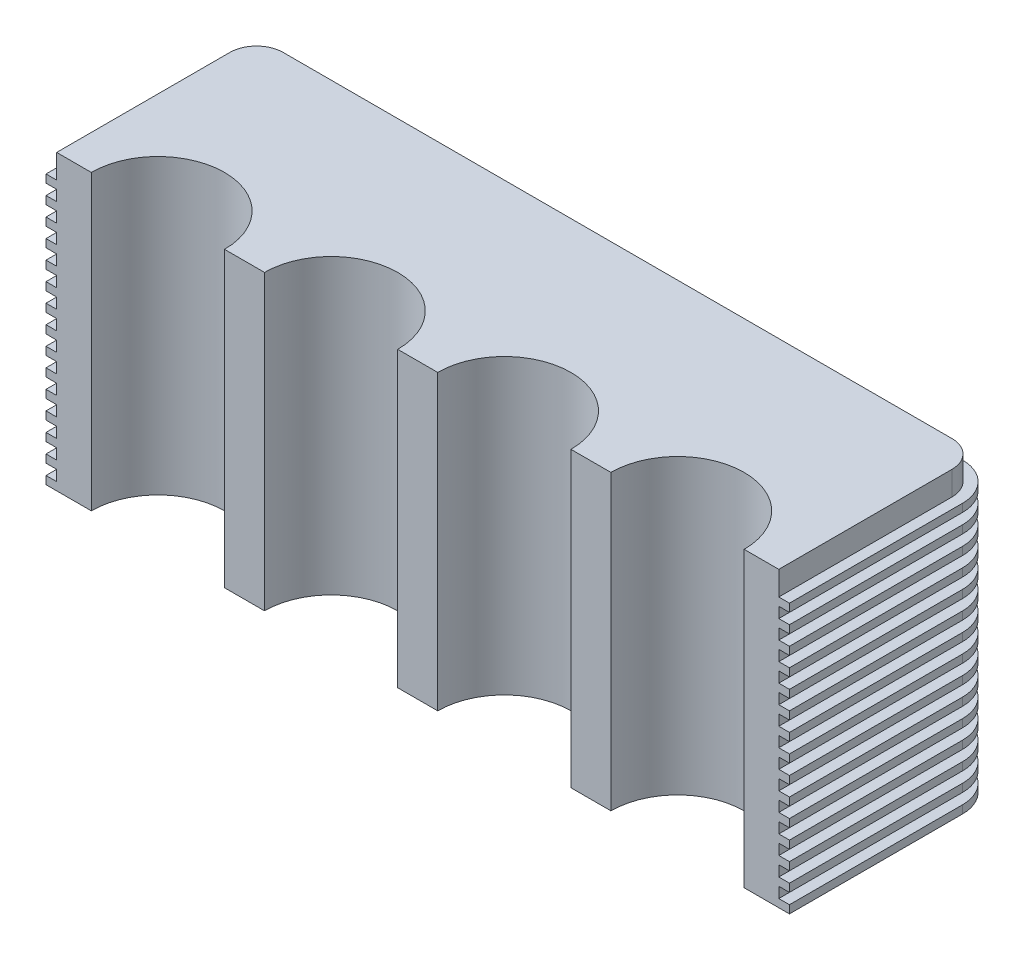
SolidWorks part; units mm, degrees
ref_plane "Front Plane" through (0, 0, 0) normal (0, 0, 1) x (1, 0, 0)
ref_plane "Top Plane" through (0, 0, 0) normal (0, 1, 0) x (1, 0, 0)
ref_plane "Right Plane" through (0, 0, 0) normal (1, 0, 0) x (0, 0, -1)
sketch "Sketch1" plane through (0, 0, 0) normal (0, 1, 0) x (1, 0, 0)
  line L0 (135.5, 0) -> (135.5, 75) construction
  line L1 (0, 0) -> (13, 0)
  line L2 (0, 0) -> (0, 65)
  line L3 (10, 75) -> (261, 75)
  line L4 (271, 0) -> (271, 65)
  line L5 (258, 0) -> (271, 0)
  line L6 (193, 0) -> (208, 0)
  line L7 (63, 0) -> (78, 0)
  line L8 (128, 0) -> (143, 0)
  arc A0 (0, 65) -> (10, 75) centre (10, 65) cw
  arc A1 (261, 75) -> (271, 65) centre (261, 65) cw
  arc A2 (258, 0) -> (208, 0) centre (233, 0) ccw
  arc A3 (193, 0) -> (143, 0) centre (168, 0) ccw
  arc A4 (13, 0) -> (63, 0) centre (38, 0) cw
  arc A5 (78, 0) -> (128, 0) centre (103, 0) cw
  dimension "D1" = 10
  dimension "D2" = 10
  dimension "D5" = 25
  dimension "D7" = 50
  dimension "D3" = 271
  dimension "D4" = 65
  dimension "D6" = 13
  dimension "D8" = 15
extrude "Boss-Extrude1" add sketch "Sketch1" along normal blind 110
sketch "Sketch2" plane through (0, 0, 0) normal (0, 1, 0) x (1, 0, 0)
  line L0 (275, 0) -> (275, 65)
  line L1 (261, 79) -> (10, 79)
  line L2 (-4, 65) -> (-4, 0)
  line L3 (271, 0) -> (275, 0)
  line L4 (0, 0) -> (-4, 0)
  line L8 (0, 65) -> (0, 0)
  line L9 (0, 0) -> (13, 0)
  line L10 (63, 0) -> (78, 0)
  line L11 (128, 0) -> (143, 0)
  line L12 (193, 0) -> (208, 0)
  line L13 (258, 0) -> (271, 0)
  line L14 (271, 0) -> (271, 65)
  line L15 (261, 75) -> (10, 75)
  line L16 (0, 65) -> (0, 0)
  line L22 (271, 0) -> (271, 65)
  line L23 (261, 75) -> (10, 75)
  arc A0 (275, 65) -> (261, 79) centre (261, 65) ccw
  arc A1 (10, 79) -> (-4, 65) centre (10, 65) ccw
  arc A6 (63, 0) -> (13, 0) centre (38, 0) ccw
  arc A7 (128, 0) -> (78, 0) centre (103, 0) ccw
  arc A8 (193, 0) -> (143, 0) centre (168, 0) ccw
  arc A9 (258, 0) -> (208, 0) centre (233, 0) ccw
  arc A10 (271, 65) -> (261, 75) centre (261, 65) ccw
  arc A11 (10, 75) -> (0, 65) centre (10, 65) ccw
  arc A16 (271, 65) -> (261, 75) centre (261, 65) ccw
  arc A17 (10, 75) -> (0, 65) centre (10, 65) ccw
  dimension "D1" = 0
  dimension "D2" = 4
extrude "Boss-Extrude2" add sketch "Sketch2" along normal blind 3
pattern_linear "LPattern1" count 15 spacing 7 along (0, 1, 0) of "Boss-Extrude2"
